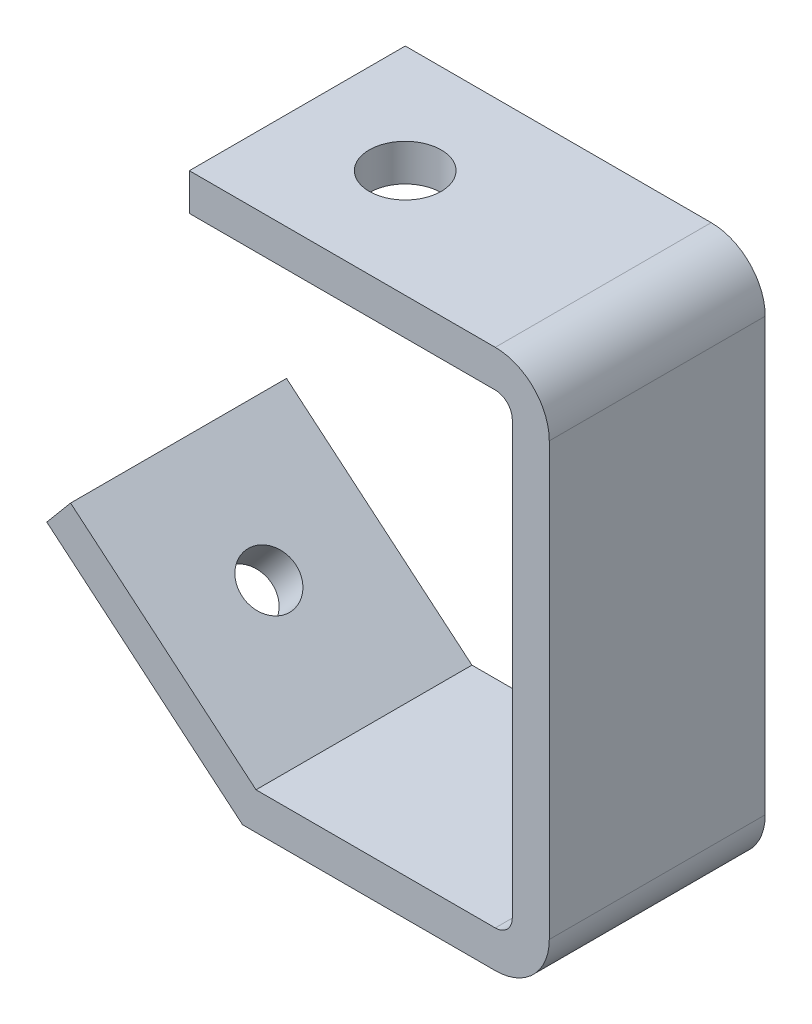
SolidWorks part; units mm, degrees
ref_plane "Front Plane" through (0, 0, 0) normal (0, 0, 1) x (1, 0, 0)
ref_plane "Top Plane" through (0, 0, 0) normal (0, 1, 0) x (1, 0, 0)
ref_plane "Right Plane" through (0, 0, 0) normal (1, 0, 0) x (0, 0, -1)
sketch "Sketch1" plane through (0, 0, 0) normal (0, 0, 1) x (1, 0, 0)
  line L0 (0, 0) -> (53.98, 0)
  line L1 (63.51, -9.53) -> (63.51, -85.72)
  line L2 (53.98, -95.25) -> (9.39, -95.25)
  line L3 (9.39, -95.25) -> (-25.1509, -66.2667)
  line L8 (0, -6.53) -> (53.98, -6.53)
  line L9 (56.98, -9.53) -> (56.98, -85.72)
  line L12 (53.98, -88.72) -> (11.7667, -88.72)
  line L13 (11.7667, -88.72) -> (-20.9535, -61.2644)
  line L14 (0, 0) -> (0, -6.53)
  line L15 (-20.9535, -61.2644) -> (-25.1509, -66.2667)
  arc A0 (53.98, 0) -> (63.51, -9.53) centre (53.98, -9.53) cw
  arc A1 (63.51, -85.72) -> (53.98, -95.25) centre (53.98, -85.72) cw
  arc A6 (53.98, -6.53) -> (56.98, -9.53) centre (53.98, -9.53) cw
  arc A7 (56.98, -85.72) -> (53.98, -88.72) centre (53.98, -85.72) cw
  dimension "D2" = 9.53
  dimension "D3" = 63.51
  dimension "D4" = 95.25
  dimension "D5" = 54.12
  dimension "D6" = 45.09
  dimension "D7" = 140
  dimension "D1" = 6.53
extrude "Boss-Extrude1" add sketch "Sketch1" along normal mid plane 38.1
sketch "Sketch2" plane through (0, 0, 0) normal (0, 1, 0) x (1, 0, 0)
  line L0 (0, -19.05) -> (0, 19.05) construction
  line L1 (53.98, 19.05) -> (0, 19.05) construction
  circle A0 centre (19.04, 0) radius 6.35
  dimension "D1" = 12.7
  dimension "D2" = 19.04
  dimension "D3" = 19.05
extrude "Cut-Extrude1" cut sketch "Sketch2" against normal up to next
sketch "Sketch3" plane through (-43.0217, -51.2713, 0) normal (-0.6428, -0.766, 0) x (0.766, -0.6428, 0)
  line L0 (23.3287, 19.05) -> (23.3287, -19.05) construction
  line L1 (23.3287, -19.05) -> (68.4187, -19.05) construction
  circle A0 centre (44.1387, 0) radius 4.765
  dimension "D1" = 9.53
  dimension "D2" = 20.81
  dimension "D3" = 19.05
extrude "Cut-Extrude2" cut sketch "Sketch3" against normal up to next
